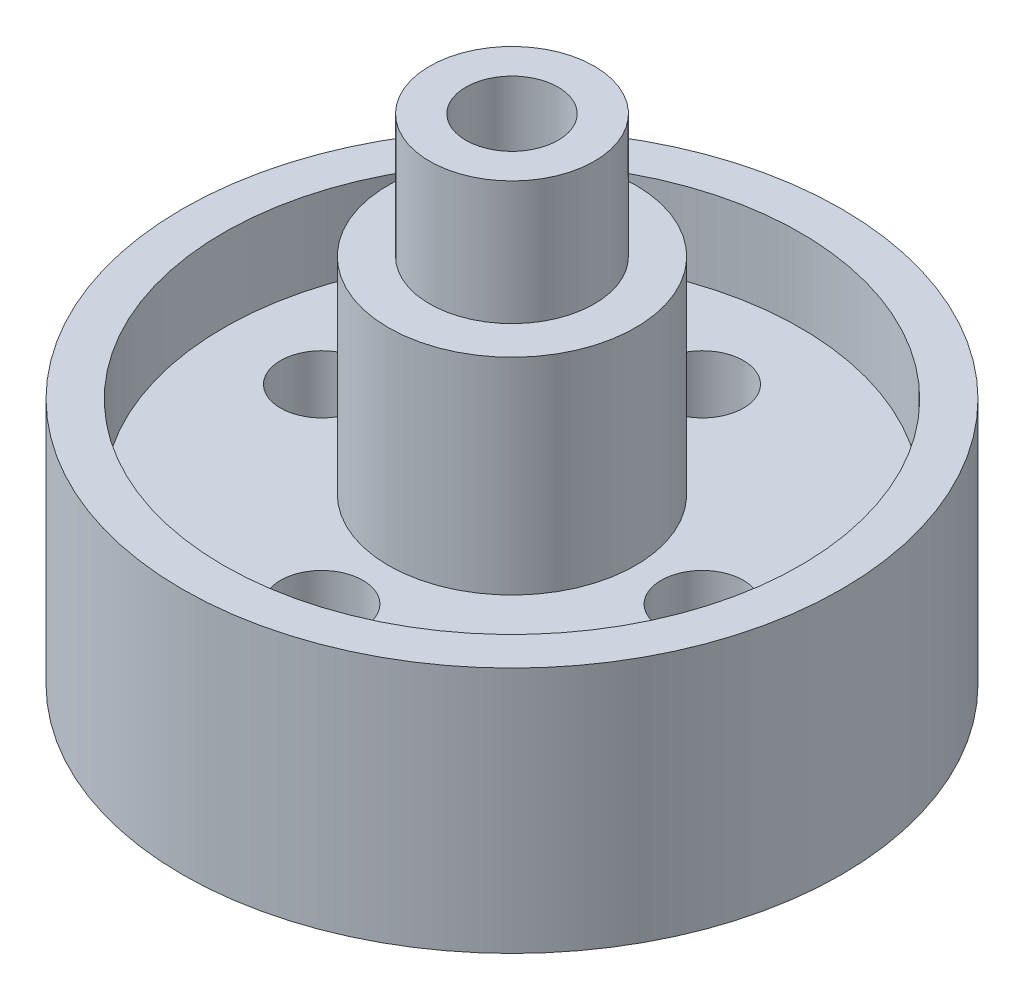
SolidWorks part; units mm, degrees
ref_plane "Front Plane" through (0, 0, 0) normal (0, 0, 1) x (1, 0, 0)
ref_plane "Top Plane" through (0, 0, 0) normal (0, 1, 0) x (1, 0, 0)
ref_plane "Right Plane" through (0, 0, 0) normal (1, 0, 0) x (0, 0, -1)
sketch "Sketch1" plane through (0, 0, 0) normal (0, 1, 0) x (1, 0, 0)
  circle A0 centre (0, 0) radius 50.8
  dimension "D1" = 101.6
extrude "Boss-Extrude1" add sketch "Sketch1" along normal blind 25.4
sketch "Sketch2" plane through (0, 25.4, 0) normal (0, 1, 0) x (1, 0, 0)
  circle A0 centre (0, 0) radius 50.8 construction
  circle A1 centre (0, 0) radius 50.8
  circle A2 centre (0, 0) radius 44.45
  dimension "D1" = 6.35
extrude "Boss-Extrude2" add sketch "Sketch2" along normal blind 12.7
sketch "Sketch3" plane through (0, 25.4, 0) normal (0, 1, 0) x (1, 0, 0)
  circle A0 centre (0, 0) radius 19.05
  dimension "D1" = 38.1
extrude "Boss-Extrude3" add sketch "Sketch3" along normal blind 31.75
sketch "Sketch4" plane through (0, 57.15, 0) normal (0, 1, 0) x (1, 0, 0)
  circle A0 centre (0, 0) radius 12.7
  dimension "D1" = 25.4
extrude "Boss-Extrude4" add sketch "Sketch4" along normal blind 19.05
sketch "Sketch5" plane through (0, 76.2, 0) normal (0, 1, 0) x (1, 0, 0)
  circle A0 centre (0, 0) radius 7.112
  dimension "D1" = 14.224
extrude "Cut-Extrude1" cut sketch "Sketch5" against normal through all
sketch "Sketch6" plane through (0, 25.4, 0) normal (0, 1, 0) x (1, 0, 0)
  line L0 (-55.5609, 0) -> (58.4011, 0) construction
  line L1 (0, 62.5726) -> (0, -61.5075) construction
  line L2 (0, 0) -> (-29.337, 0) construction
  circle A0 centre (-29.337, 0) radius 6.35
  circle A1 centre (0, 0) radius 29.337 construction
  circle A2 centre (0, 29.337) radius 6.35
  circle A3 centre (29.337, 0) radius 6.35
  circle A4 centre (0, -29.337) radius 6.35
  point P9 (0, 0)
  point P10 (0, 0)
  dimension "D1" = 12.7
  dimension "D2" = 58.674
  dimension "D4" = 29.337
  dimension "D3" = 4
extrude "Cut-Extrude2" cut sketch "Sketch6" against normal through all
